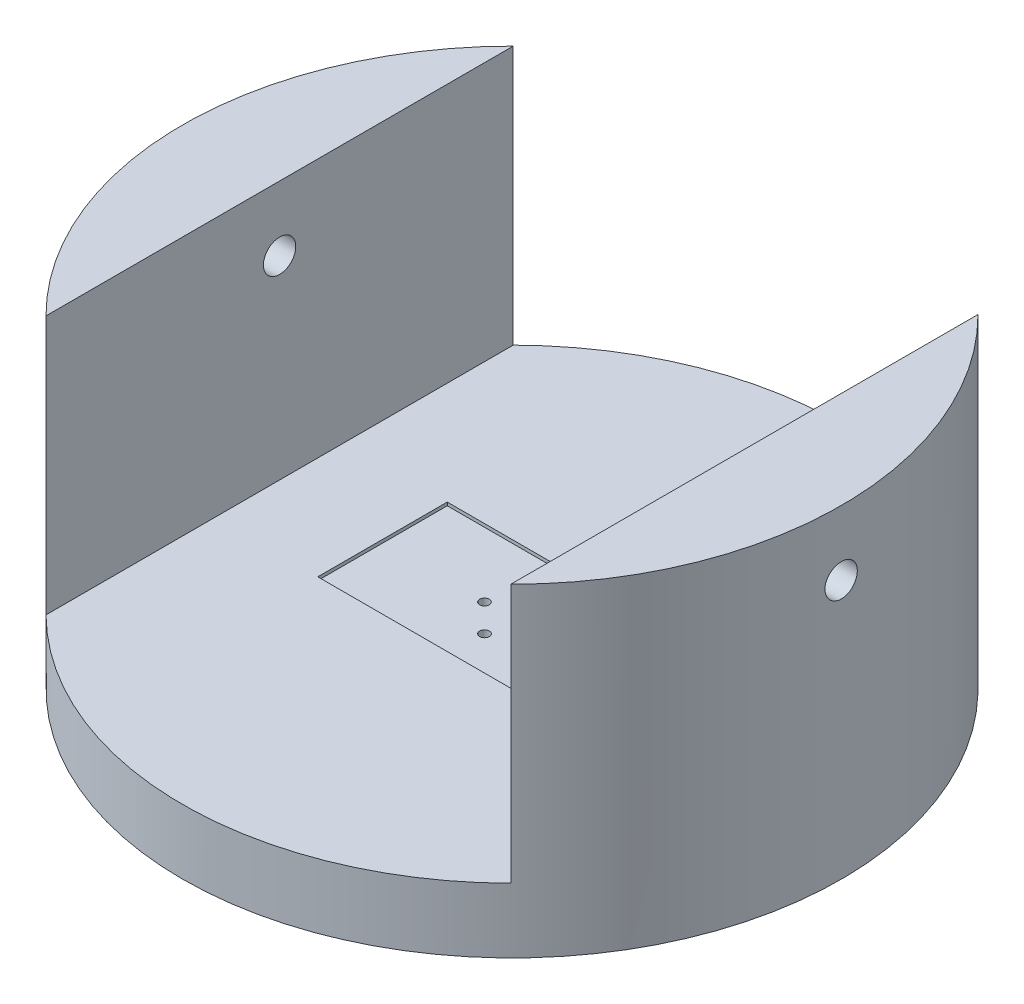
SolidWorks part; units mm, degrees
ref_plane "Front Plane" through (0, 0, 0) normal (0, 0, 1) x (1, 0, 0)
ref_plane "Top Plane" through (0, 0, 0) normal (0, 1, 0) x (1, 0, 0)
ref_plane "Right Plane" through (0, 0, 0) normal (1, 0, 0) x (0, 0, -1)
sketch "Sketch1" plane through (0, 0, 0) normal (0, 1, 0) x (1, 0, 0)
  circle A0 centre (0, 0) radius 50.9
  dimension "D1" = 101.8
extrude "Boss-Extrude1" add sketch "Sketch1" along normal blind 10
sketch "Sketch2" plane through (0, 10, 0) normal (0, 1, 0) x (1, 0, 0)
  line L0 (-70.1077, 0) -> (74.3956, 0) construction
  line L1 (-35.9, 36.0832) -> (-35.9, -36.0832)
  line L2 (0, 67.2073) -> (0, -61.19) construction
  line L3 (35.9, 36.0832) -> (35.9, -36.0832)
  circle A0 centre (0, 0) radius 50.9 construction
  arc A1 (-35.9, 36.0832) -> (-35.9, -36.0832) centre (0, 0) ccw
  arc A2 (35.9, 36.0832) -> (35.9, -36.0832) centre (0, 0) cw
  point P7 (-50.9, 0)
  dimension "D1" = 15
extrude "Boss-Extrude2" add sketch "Sketch2" along normal blind 40
sketch "Sketch3" plane through (0, 10, 0) normal (0, 1, 0) x (1, 0, 0)
  line L0 (50.9, 0) -> (-50.9, 0) construction
  line L1 (35.9, 36.0832) -> (35.9, -36.0832) construction
  line L2 (-35.9, -36.0832) -> (-35.9, 36.0832) construction
  line L3 (-20, 10) -> (20, 10)
  line L4 (20, 10) -> (20, -10)
  line L5 (20, -10) -> (-20, -10)
  line L6 (-20, -10) -> (-20, 10)
  line L8 (0, 50.9) -> (0, -50.9) construction
  arc A0 (35.9, -36.0832) -> (35.9, 36.0832) centre (0, 0) ccw construction
  arc A1 (-35.9, 36.0832) -> (-35.9, -36.0832) centre (0, 0) ccw construction
  arc A2 (35.9, 36.0832) -> (-35.9, 36.0832) centre (0, 0) ccw construction
  arc A3 (-35.9, -36.0832) -> (35.9, -36.0832) centre (0, 0) ccw construction
  point P26 (20, 0)
  point P27 (0, 10)
  dimension "D1" = 40
  dimension "D2" = 20
extrude "Cut-Extrude1" cut sketch "Sketch3" against normal blind 0.5
sketch "Sketch4" plane through (35.9, 0, 0) normal (-1, 0, 0) x (0, 0, 1)
  line L0 (0, 50) -> (0, 0) construction
  line L1 (36.0832, 50) -> (-36.0832, 50) construction
  circle A0 centre (0, 40) radius 2.5
  dimension "D1" = 5
  dimension "D2" = 10
extrude "Cut-Extrude2" cut sketch "Sketch4" against normal through all both and the other way through all
sketch "Sketch5" plane through (0, 0, 0) normal (0, -1, 0) x (1, 0, 0)
  line L0 (-50.9, 0) -> (50.9, 0) construction
  line L1 (0, 50.9) -> (0, -50.9) construction
  circle A0 centre (0, 0) radius 50.9 construction
  circle A2 centre (-4.25, 0) radius 0.75
  circle A3 centre (0, 4.25) radius 0.75
  circle A4 centre (4.25, 0) radius 0.75
  circle A5 centre (0, -4.25) radius 0.75
  dimension "D1" = 8.5
  dimension "D2" = 1.5
  dimension "D3" = 1.5
  dimension "D4" = 1.5
  dimension "D5" = 1.5
  dimension "D6" = 8.5
extrude "Cut-Extrude3" cut sketch "Sketch5" against normal through all
